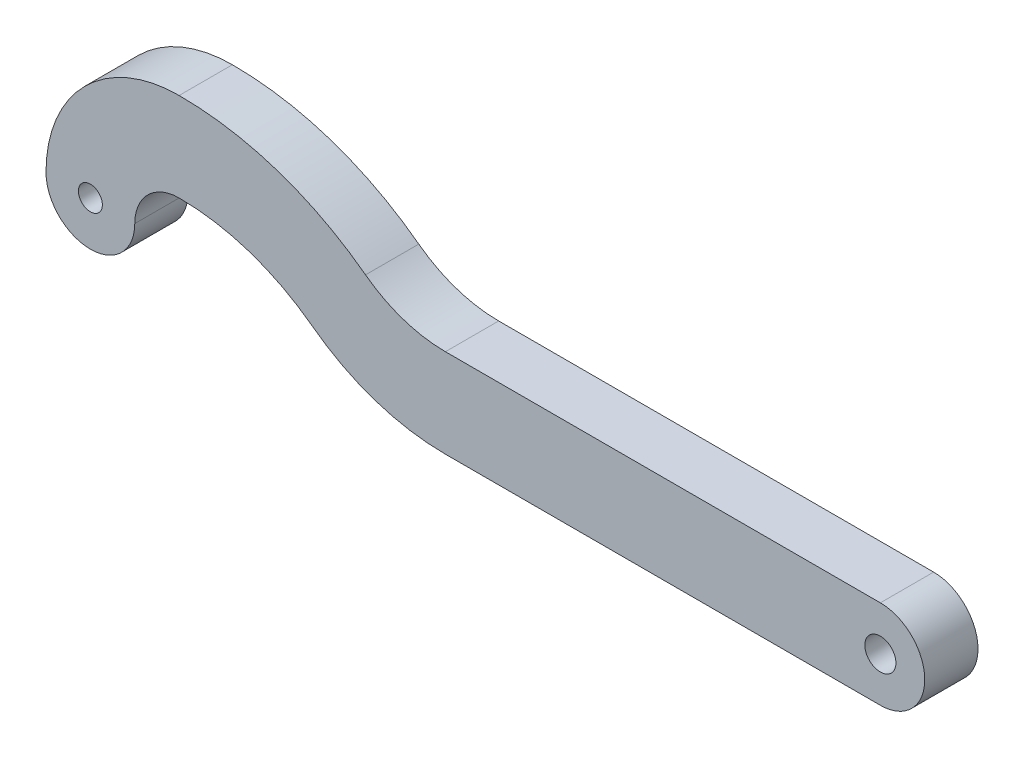
SolidWorks part; units mm, degrees
ref_plane "Plan de face" through (0, 0, 0) normal (0, 0, 1) x (1, 0, 0)
ref_plane "Plan de dessus" through (0, 0, 0) normal (0, 1, 0) x (1, 0, 0)
ref_plane "Plan de droite" through (0, 0, 0) normal (1, 0, 0) x (0, 0, -1)
sketch "Esquisse1" plane through (0, 0, 0) normal (0, 0, 1) x (1, 0, 0)
  line L0 (0, 10) -> (40, 10) construction
  line L2 (0, 0) -> (0, 10) construction
  line L3 (40, 10) -> (89, 10)
  line L4 (89, 0) -> (89, 10) construction
  line L5 (40, 0) -> (89, 0)
  line L6 (0, 0) -> (40, 0) construction
  line L7 (0, 5) -> (-5, 5) construction
  line L8 (-5, 5) -> (-5, 10) construction
  line L9 (5, 5) -> (5, 10) construction
  line L10 (0, 5) -> (89, 5) construction
  line L11 (10, 5) -> (10, 10) construction
  line L12 (10, 10) -> (10, 20) construction
  arc A0 (-5, 5) -> (0, 0) centre (0, 5) ccw
  arc A1 (89, 10) -> (89, 0) centre (89, 5) cw
  circle A2 centre (0, 5) radius 1.35
  circle A3 centre (89, 5) radius 1.75
  arc A10 (0, 10) -> (-5, 5) centre (0, 5) ccw construction
  arc A11 (0, 0) -> (5, 5) centre (0, 5) ccw
  arc A12 (5, 5) -> (10, 10) centre (10, 5) cw
  arc A13 (-5, 5) -> (10, 20) centre (10, 5) cw
  arc A14 (10, 10) -> (25, 5) centre (10, -15) cw
  arc A15 (25, 5) -> (40, 0) centre (40, 25) ccw
  arc A16 (10, 20) -> (31, 13) centre (10, -15) cw
  arc A17 (31, 13) -> (40, 10) centre (40, 25) ccw
  point P25 (30.8568, 12.9483)
  point P26 (0, 0)
  point P27 (21.2742, 13.984)
  point P28 (26.9191, 12.3526)
  dimension "D3" = 2.7
  dimension "D4" = 3.5
  dimension "D1" = 10
  dimension "D2" = 89
  dimension "D5" = 10
  dimension "D6" = 20
extrude "Boss.-Extru.1" add sketch "Esquisse1" along normal blind 6
chamfer "Chanfrein1" distance 1.25 angle 45 1 edges at (90.75, 5, 0)
